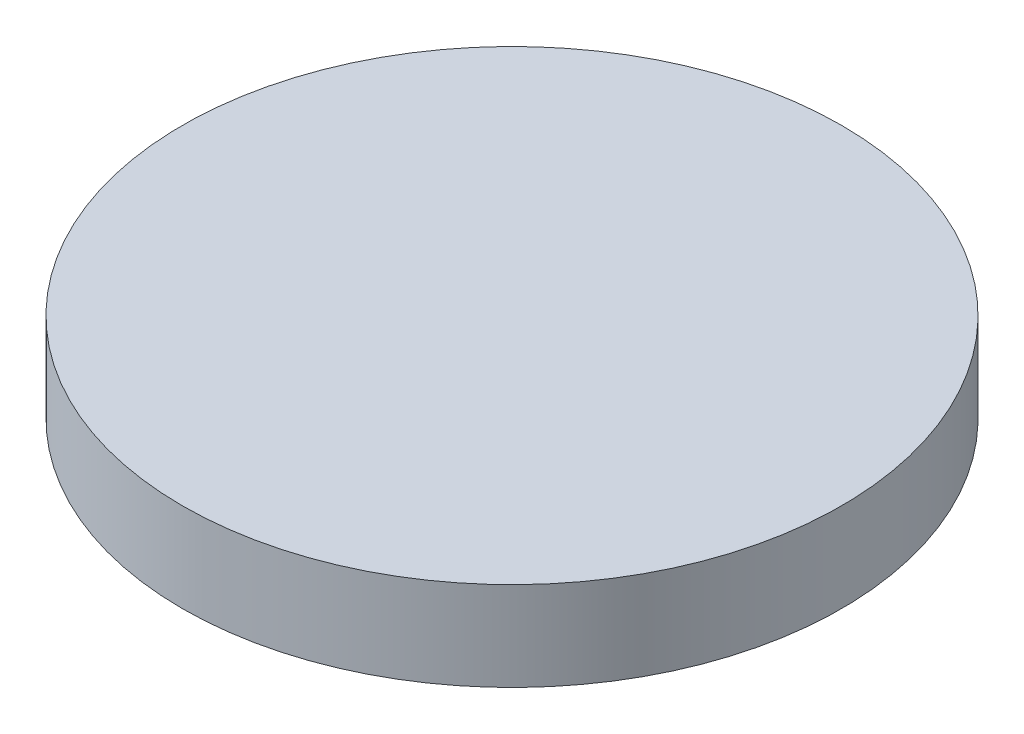
SolidWorks part; units mm, degrees
ref_plane "Front Plane" through (0, 0, 0) normal (0, 0, 1) x (1, 0, 0)
ref_plane "Top Plane" through (0, 0, 0) normal (0, 1, 0) x (1, 0, 0)
ref_plane "Right Plane" through (0, 0, 0) normal (1, 0, 0) x (0, 0, -1)
sketch "Sketch1" plane through (0, 0, 0) normal (0, 1, 0) x (1, 0, 0)
  circle A0 centre (0, 0) radius 3.7
  dimension "D1" = 7.4
extrude "Boss-Extrude1" add sketch "Sketch1" along normal blind 1
